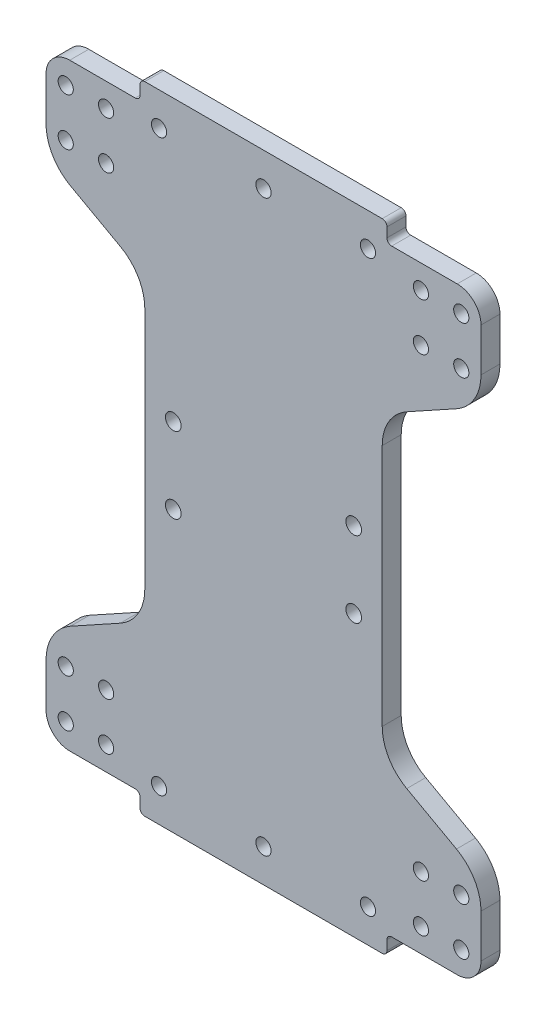
SolidWorks part; units mm, degrees
material "Acrylic (Medium-high impact)"
ref_plane "Front Plane" through (0, 0, 0) normal (0, 0, 1) x (1, 0, 0)
ref_plane "Top Plane" through (0, 0, 0) normal (0, 1, 0) x (1, 0, 0)
ref_plane "Right Plane" through (0, 0, 0) normal (1, 0, 0) x (0, 0, -1)
sketch "Sketch1" plane through (0, 0, 0) normal (0, 0, 1) x (1, 0, 0)
  line L0 (1.25, 62.9364) -> (93.1655, 62.9364) construction
  line L1 (1.4077, -0.0636) -> (20.2069, -0.0636)
  line L2 (1.4077, -0.0636) -> (1.4077, 19.9364)
  line L3 (69.2085, 2.9364) -> (69.2085, -10.0636) construction
  line L4 (80.3577, 4.9364) -> (80.3577, 14.9364) construction
  line L5 (1.4077, 19.9364) -> (22.2077, 31.43)
  line L6 (25.2069, 2.9364) -> (47.2077, 2.9364) construction
  line L7 (88.8577, 14.9364) -> (80.3577, 14.9364) construction
  line L8 (47.2077, -14.0636) -> (47.2077, 139.9364) construction
  line L9 (88.8577, 4.9364) -> (88.8577, 14.9364) construction
  line L10 (21.2069, -1.0636) -> (21.2069, -3.0636)
  line L11 (22.2077, 94.4428) -> (22.2077, 31.43)
  line L12 (88.8577, 4.9364) -> (80.3577, 4.9364) construction
  line L13 (80.3577, 9.9364) -> (88.8577, 9.9364) construction
  line L14 (14.0577, 9.9364) -> (5.5577, 9.9364) construction
  line L15 (5.5577, 4.9364) -> (14.0577, 4.9364) construction
  line L16 (5.5577, 4.9364) -> (5.5577, 14.9364) construction
  line L17 (5.5577, 14.9364) -> (14.0577, 14.9364) construction
  line L18 (14.0577, 4.9364) -> (14.0577, 14.9364) construction
  line L19 (72.2077, 94.4428) -> (72.2077, 31.43)
  line L20 (73.2085, -1.0636) -> (73.2085, -3.0636)
  line L21 (93.0077, 19.9364) -> (72.2077, 31.43)
  line L22 (93.0077, -0.0636) -> (93.0077, 19.9364)
  line L23 (93.0077, -0.0636) -> (74.2085, -0.0636)
  line L24 (25.2069, 122.9364) -> (25.2069, 135.9364) construction
  line L25 (14.0577, 120.9364) -> (14.0577, 110.9364) construction
  line L26 (5.5577, 110.9364) -> (14.0577, 110.9364) construction
  line L27 (5.5577, 120.9364) -> (5.5577, 110.9364) construction
  line L28 (5.5577, 120.9364) -> (14.0577, 120.9364) construction
  line L29 (14.0577, 115.9364) -> (5.5577, 115.9364) construction
  line L30 (80.3577, 115.9364) -> (88.8577, 115.9364) construction
  line L31 (88.8577, 120.9364) -> (80.3577, 120.9364) construction
  line L32 (88.8577, 120.9364) -> (88.8577, 110.9364) construction
  line L33 (88.8577, 110.9364) -> (80.3577, 110.9364) construction
  line L34 (25.2069, 122.9364) -> (47.2077, 122.9364) construction
  line L35 (22.2069, 129.9364) -> (72.2085, 129.9364)
  line L36 (80.3577, 120.9364) -> (80.3577, 110.9364) construction
  line L37 (69.2085, 122.9364) -> (69.2085, 135.9364) construction
  line L38 (25.2069, 2.9364) -> (25.2069, -10.0636) construction
  line L39 (73.2085, 126.9364) -> (73.2085, 128.9364)
  line L40 (93.0077, 125.9364) -> (74.2085, 125.9364)
  line L41 (93.0077, 125.9364) -> (93.0077, 105.9364)
  line L42 (93.0077, 105.9364) -> (72.2077, 94.4428)
  line L43 (21.2069, 126.9364) -> (21.2069, 128.9364)
  line L45 (1.4077, 105.9364) -> (22.2077, 94.4428)
  line L46 (1.4077, 125.9364) -> (1.4077, 105.9364)
  line L47 (1.4077, 125.9364) -> (20.2069, 125.9364)
  line L48 (22.2069, -4.0636) -> (72.2085, -4.0636)
  circle A0 centre (5.5577, 4.9364) radius 1.6
  circle A1 centre (14.0577, 4.9364) radius 1.6
  circle A2 centre (14.0577, 14.9364) radius 1.6
  circle A3 centre (5.5577, 14.9364) radius 1.6
  arc A4 (72.2085, -4.0636) -> (73.2085, -3.0636) centre (72.2085, -3.0636) ccw
  arc A5 (73.2085, -1.0636) -> (74.2085, -0.0636) centre (74.2085, -1.0636) cw
  arc A6 (22.2069, -4.0636) -> (21.2069, -3.0636) centre (22.2069, -3.0636) cw
  circle A7 centre (69.2085, 2.9364) radius 1.6
  circle A8 centre (47.2069, 2.9364) radius 1.6
  circle A9 centre (66.2077, 54.9364) radius 1.65
  circle A10 centre (88.8577, 14.9364) radius 1.6
  circle A11 centre (80.3577, 14.9364) radius 1.6
  circle A12 centre (80.3577, 4.9364) radius 1.6
  circle A13 centre (88.8577, 4.9364) radius 1.6
  arc A14 (22.2069, 129.9364) -> (21.2069, 128.9364) centre (22.2069, 128.9364) ccw
  arc A15 (21.2069, 126.9364) -> (20.2069, 125.9364) centre (20.2069, 126.9364) cw
  circle A16 centre (28.2077, 54.9364) radius 1.65
  arc A17 (72.2085, 129.9364) -> (73.2085, 128.9364) centre (72.2085, 128.9364) cw
  circle A18 centre (25.2069, 2.9364) radius 1.6
  circle A19 centre (25.2069, 122.9364) radius 1.6
  circle A20 centre (28.2077, 70.9364) radius 1.65
  circle A22 centre (88.8577, 120.9364) radius 1.6
  arc A23 (21.2069, -1.0636) -> (20.2069, -0.0636) centre (20.2069, -1.0636) ccw
  circle A25 centre (80.3577, 120.9364) radius 1.6
  circle A26 centre (80.3577, 110.9364) radius 1.6
  circle A27 centre (88.8577, 110.9364) radius 1.6
  circle A28 centre (66.2077, 70.9364) radius 1.65
  circle A29 centre (47.2069, 122.9364) radius 1.6
  circle A30 centre (69.2085, 122.9364) radius 1.6
  arc A32 (73.2085, 126.9364) -> (74.2085, 125.9364) centre (74.2085, 126.9364) ccw
  circle A34 centre (5.5577, 110.9364) radius 1.6
  circle A35 centre (14.0577, 110.9364) radius 1.6
  circle A36 centre (14.0577, 120.9364) radius 1.6
  circle A37 centre (5.5577, 120.9364) radius 1.6
  point P61 (47.2077, 62.9364)
  point P108 (72.2077, 62.9364)
  point P109 (22.2077, 62.9364)
  dimension "D10" = 3.2
  dimension "D15" = 3.2
  dimension "D5" = 45.8
  dimension "D32" = 1
  dimension "D17" = 1
  dimension "D1" = 63
  dimension "D2" = 19
  dimension "D3" = 20
  dimension "D4" = 8
  dimension "D6" = 10
  dimension "D7" = 8.5
  dimension "D8" = 53
  dimension "D9" = 4.15
  dimension "D11" = 13
  dimension "D12" = 7
  dimension "D13" = 22
  dimension "D14" = 25
  dimension "D16" = 4
extrude "Boss-Extrude1" add sketch "Sketch1" along normal blind 4
fillet "Fillet2" radius 10 8 edges at (1.4077, 19.9364, 2) (22.2077, 31.43, 2) (93.0077, 19.9364, 2) (72.2077, 31.43, 2) (93.0077, 105.9364, 2) (72.2077, 94.4428, 2) (1.4077, 105.9364, 2) (22.2077, 94.4428, 2)
fillet "Fillet3" radius 5 4 edges at (1.4077, -0.0636, 2) (1.4077, 125.9364, 2) (93.0077, 125.9364, 2) (93.0077, -0.0636, 2)
